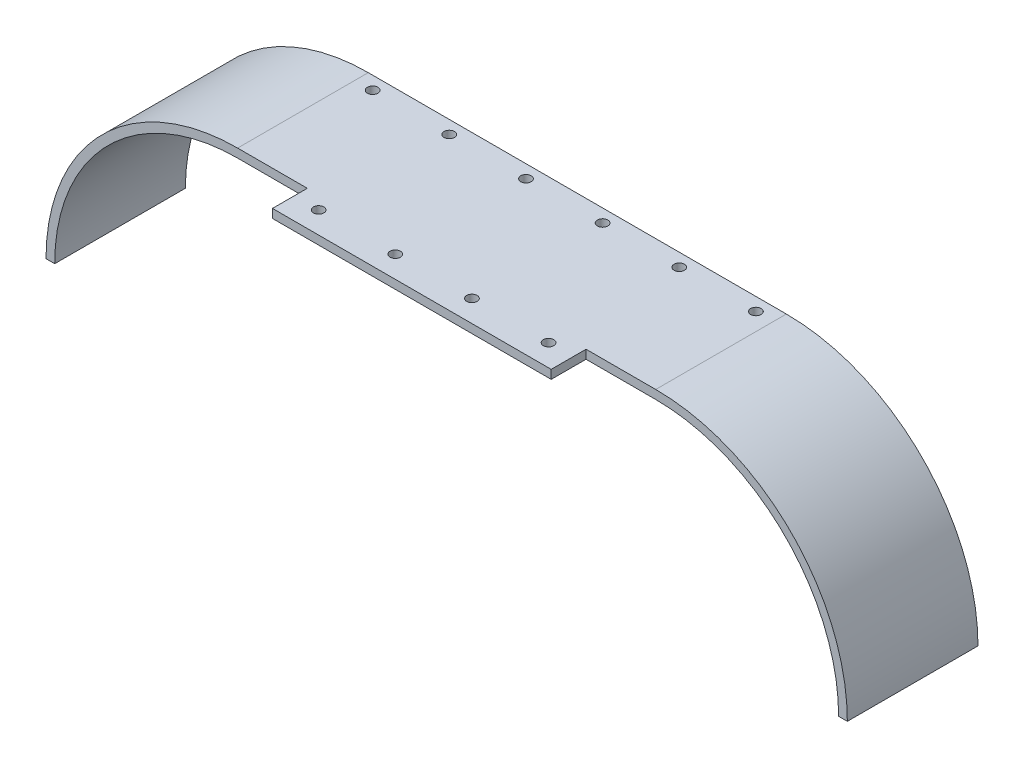
SolidWorks part; units mm, degrees
ref_plane "Front Plane" through (0, 0, 0) normal (0, 0, 1) x (1, 0, 0)
ref_plane "Top Plane" through (0, 0, 0) normal (0, 1, 0) x (1, 0, 0)
ref_plane "Right Plane" through (0, 0, 0) normal (1, 0, 0) x (0, 0, -1)
sketch "Sketch1" plane through (0, 0, 0) normal (0, 0, 1) x (1, 0, 0)
  line L0 (-60, 52.5) -> (60, 52.5)
  line L4 (-60, 55) -> (60, 55)
  line L6 (-123.3493, 0) -> (118.9409, 0)
  line L7 (0, -60.5) -> (0, 60.5) construction
  arc A0 (-60, 52.5) -> (-112.5, 0) centre (-60, 0) ccw
  arc A1 (-60, 55) -> (-115, 0) centre (-60, 0) ccw
  arc A2 (60, 55) -> (115, 0) centre (60, 0) cw
  arc A3 (60, 52.5) -> (112.5, 0) centre (60, 0) cw
  point P13 (0, 52.5)
  point P17 (0, 55)
  dimension "D1" = 105
  dimension "D2" = 110
  dimension "D3" = 60
extrude "Boss-Extrude2" add sketch "Sketch1" along normal blind 37.5 contours L0 A3 L6 A2 L4 A1 A0
sketch "Sketch2" plane through (0, 0, 37.5) normal (0, 0, 1) x (1, 0, 0)
  line L0 (-60, 55) -> (60, 55) construction
  line L1 (-40, 55) -> (40, 55)
  line L2 (-40, 55) -> (-40, 52.5)
  line L3 (-40, 52.5) -> (40, 52.5)
  line L4 (40, 55) -> (40, 52.5)
  line L5 (-60, 52.5) -> (60, 52.5) construction
  point P8 (0, 52.5)
  dimension "D1" = 80
  dimension "D2" = 2.5
extrude "Boss-Extrude3" add sketch "Sketch2" along normal blind 10
sketch "Sketch3" plane through (0, 55, 0) normal (0, 1, 0) x (1, 0, 0)
  line L0 (-45.3384, -37.5) -> (-45.3384, -41.25) construction
  line L1 (-60, -37.5) -> (-40, -37.5) construction
  line L2 (-45.3384, -41.25) -> (51.6777, -41.25) construction
  circle A0 centre (-55, -41.25) radius 1.5 construction
  circle A1 centre (-44, -41.25) radius 1.5 [skipped]
  circle A2 centre (-33, -41.25) radius 1.5
  circle A3 centre (-22, -41.25) radius 1.5 [skipped]
  circle A4 centre (-11, -41.25) radius 1.5
  circle A5 centre (0, -41.25) radius 1.5 [skipped]
  circle A6 centre (11, -41.25) radius 1.5
  circle A8 centre (33, -41.25) radius 1.5
  circle A9 centre (22, -41.25) radius 1.5 construction
  dimension "D2" = 3
  dimension "D1" = 3.75
  dimension "D3" = 55
  dimension "D4" = 9
extrude "Cut-Extrude1" cut sketch "Sketch3" against normal blind 10
sketch "Sketch4" plane through (0, 55, 0) normal (0, 1, 0) x (1, 0, 0)
  line L0 (-38.8585, 0) -> (-38.8585, -3.75) construction
  line L1 (-60, 0) -> (60, 0) construction
  line L2 (0, -3.75) -> (-55, -3.75) construction
  circle A0 centre (-55, -3.75) radius 1.5
  circle A1 centre (-33, -3.75) radius 1.5
  circle A2 centre (-11, -3.75) radius 1.5
  circle A3 centre (11, -3.75) radius 1.5
  circle A4 centre (33, -3.75) radius 1.5
  circle A5 centre (55, -3.75) radius 1.5
  dimension "D3" = 3
  dimension "D1" = 3.75
  dimension "D2" = 55
  dimension "D4" = 6
extrude "Cut-Extrude2" cut sketch "Sketch4" against normal blind 10
